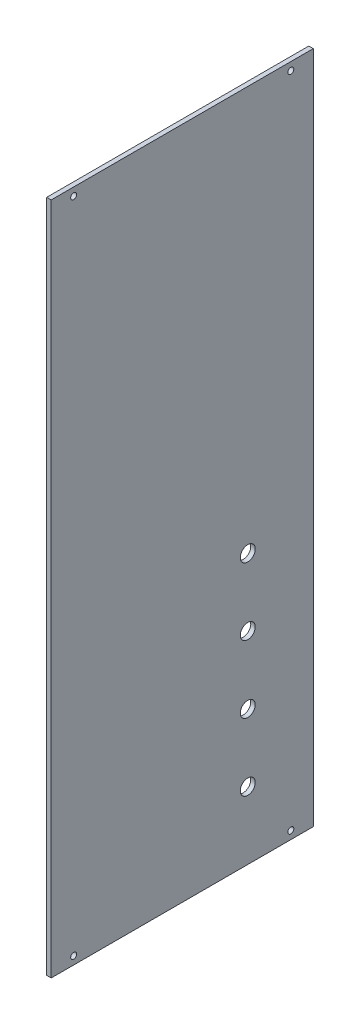
SolidWorks part; units mm, degrees
ref_plane "Front Plane" through (0, 0, 0) normal (0, 0, 1) x (1, 0, 0)
ref_plane "Top Plane" through (0, 0, 0) normal (0, 1, 0) x (1, 0, 0)
ref_plane "Right Plane" through (0, 0, 0) normal (1, 0, 0) x (0, 0, -1)
sketch "Sketch1" plane through (0, 0, 0) normal (1, 0, 0) x (0, 0, -1)
  line L1 (-87.5, 225) -> (87.5, 225)
  line L2 (-87.5, 225) -> (-87.5, -225)
  line L3 (-87.5, -225) -> (87.5, -225)
  line L4 (87.5, 225) -> (87.5, -225)
  line L5 (-87.5, 225) -> (87.5, -225) construction
  line L6 (-87.5, -225) -> (87.5, 225) construction
  line L7 (72.5, -219.6681) -> (-72.5, -219.6681) construction
  line L8 (72.5, -219.6681) -> (72.5, 219.6681) construction
  line L9 (72.5, 219.6681) -> (-72.5, 219.6681) construction
  line L10 (-72.5, -219.6681) -> (-72.5, 219.6681) construction
  line L11 (72.5, -219.6681) -> (-72.5, 219.6681) construction
  line L12 (72.5, 219.6681) -> (-72.5, -219.6681) construction
  circle A0 centre (-72.5, 219.6681) radius 2
  circle A1 centre (72.5, 219.6681) radius 2
  circle A2 centre (72.5, -219.6681) radius 2
  circle A3 centre (-72.5, -219.6681) radius 2
  circle A4 centre (72.5, 219.6681) radius 1.9 construction
  point P0 (0, 0)
  point P6 (0, 0)
  point P15 (33.4819, 86.1198)
  point P16 (32.5252, 121.6551)
  point P17 (33.0979, 119.0228)
  dimension "D1" = 4
  dimension "D2" = 175
  dimension "D3" = 450
extrude "Boss-Extrude1" add sketch "Sketch1" along normal blind 3
sketch "Sketch2" plane through (0, 0, 0) normal (1, 0, 0) x (0, 0, -1)
  line L0 (0, 0) -> (0, -225) construction
  line L2 (0, 0) -> (87.5, 0) construction
  line L3 (87.5, -225) -> (87.5, 225) construction
  line L4 (-87.5, -225) -> (87.5, -225) construction
  line L5 (43.75, 0) -> (43.75, -225) construction
  line L6 (0, -112.5) -> (87.5, -112.5) construction
  circle A0 centre (43.75, -90) radius 5
  circle A1 centre (43.75, -45) radius 5
  circle A4 centre (43.75, -135) radius 5
  circle A5 centre (43.75, -180) radius 5
  point P18 (43.75, -112.5)
  dimension "D1" = 10
  dimension "D2" = 112.5
  dimension "D3" = 22.5
  dimension "D4" = 45
extrude "RCA_Holes" cut sketch "Sketch2" along normal through all
equation "\"D3@Sketch2\"=\"D2@Sketch2\"/5"
equation "\"D4@Sketch2\"=\"D2@Sketch2\"/5*2"
